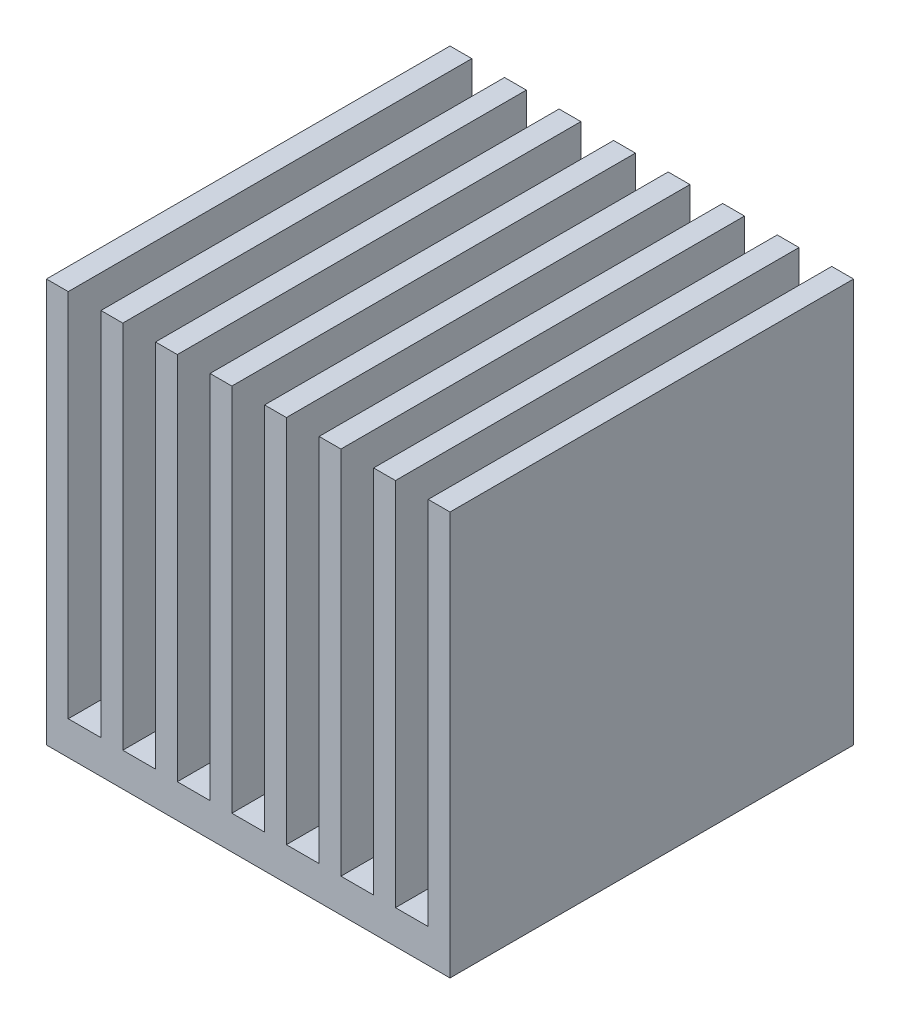
SolidWorks part; units mm, degrees
ref_plane "Front Plane" through (0, 0, 0) normal (0, 0, 1) x (1, 0, 0)
ref_plane "Top Plane" through (0, 0, 0) normal (0, 1, 0) x (1, 0, 0)
ref_plane "Right Plane" through (0, 0, 0) normal (1, 0, 0) x (0, 0, -1)
sketch "Sketch1" plane through (0, 0, 0) normal (0, 1, 0) x (1, 0, 0)
  line L1 (0, 0) -> (-12, 0)
  line L2 (0, 0) -> (0, -12)
  line L3 (0, -12) -> (-12, -12)
  line L4 (-12, 0) -> (-12, -12)
  dimension "D1" = 12
  dimension "D2" = 12
extrude "Boss-Extrude1" add sketch "Sketch1" along normal blind 12
sketch "Sketch2" plane through (0, 0, 12) normal (0, 0, 1) x (1, 0, 0)
  line L1 (-11.3514, 1) -> (-10.3784, 1)
  line L6 (-12, 12) -> (-12, 0) construction
  line L9 (-11.3514, 1) -> (-11.3514, 12)
  line L10 (-12, 12) -> (0, 12) construction
  line L11 (-10.3784, 12) -> (-10.3784, 1)
  line L12 (-11.3514, 12) -> (-10.3784, 12)
  dimension "D2" = 0.6486
  dimension "D3" = 0.973
  dimension "D1" = 11
extrude "Cut-Extrude1" cut sketch "Sketch2" against normal through all
pattern_linear "LPattern1" count 7 spacing 1.6216 along (1, 0, 0) of "Cut-Extrude1"
equation "\"FinHeight\"= 11mm"
equation "\"D1@Boss-Extrude1\"=\"FinHeight\"+\"BaseThickness\""
equation "\"BaseThickness\"= 1mm"
equation "\"FinNumber\"= 8"
equation "\"D2@Sketch2\"=\"FinWidth\""
equation "\"D3@Sketch2\"=\"FinGapRatio\"*\"FinWidth\""
equation "\"D1@Sketch2\"=\"FinHeight\""
equation "\"D1@LPattern1\"=\"FinNumber\"-1"
equation "\"D3@LPattern1\"=\"FinWidth\"*(\"FinGapRatio\"+1)"
equation "\"FinGapRatio\"= 1.5"
equation "\"NumberOfPortions\"= ( \"FinGapRatio\" + 1 ) * ( \"FinNumber\" - 1 ) + 1"
equation "\"FinWidth\"= \"BaseLengthPerpendicularFin\" / \"NumberOfPortions\""
equation "\"BaseLength\"= 12mm"
equation "\"BaseLengthPerpendicularFin\"= 12mm"
equation "\"D1@Sketch1\"=\"BaseLength\""
equation "\"D2@Sketch1\"=\"BaseLengthPerpendicularFin\""
